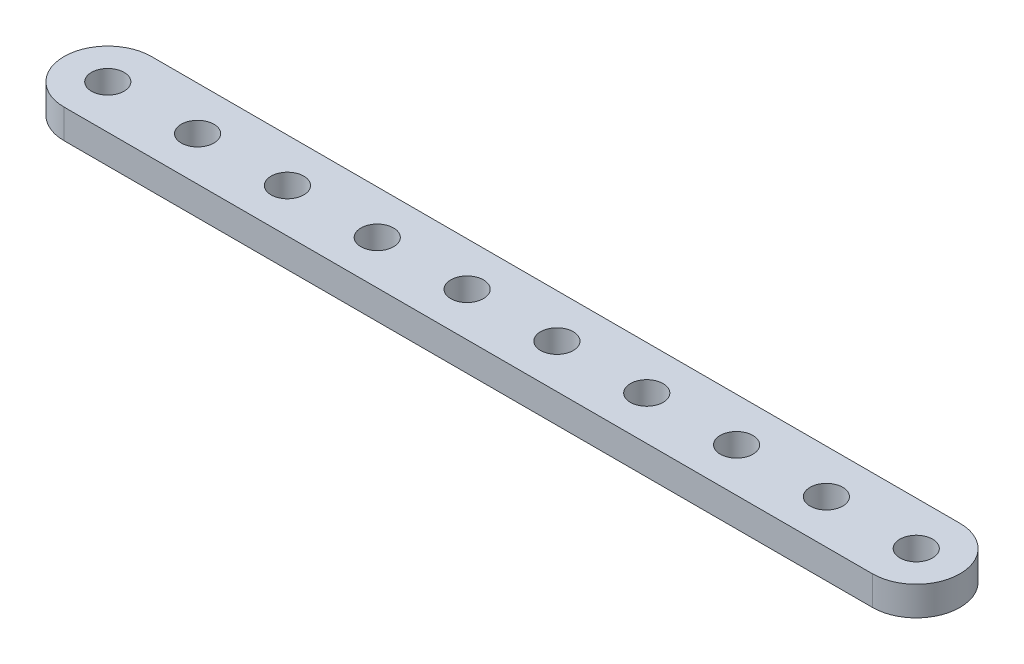
SolidWorks part; units mm, degrees
ref_plane "Front Plane" through (0, 0, 0) normal (0, 0, 1) x (1, 0, 0)
ref_plane "Top Plane" through (0, 0, 0) normal (0, 1, 0) x (1, 0, 0)
ref_plane "Right Plane" through (0, 0, 0) normal (1, 0, 0) x (0, 0, -1)
ref_plane "Plane1" through (0, 0, 0) normal (0, -1, 0) x (1, 0, 0)
sketch "Sketch1" plane through (0, 0, 0) normal (0, -1, 0) x (1, 0, 0)
  line L0 (-48.895, -4.7625) -> (48.895, -4.7625)
  line L1 (48.895, 4.7625) -> (-48.895, 4.7625)
  arc A0 (48.895, -4.7625) -> (48.895, 4.7625) centre (48.895, 0) ccw
  arc A1 (-48.895, 4.7625) -> (-48.895, -4.7625) centre (-48.895, 0) ccw
  circle A2 centre (48.895, 0) radius 1.778
  circle A3 centre (39.116, 0) radius 1.778
  circle A4 centre (29.337, 0) radius 1.778
  circle A5 centre (19.558, 0) radius 1.778
  circle A6 centre (9.779, 0) radius 1.778
  circle A7 centre (0, 0) radius 1.778
  circle A8 centre (-9.779, 0) radius 1.778
  circle A9 centre (-19.558, 0) radius 1.778
  circle A10 centre (-29.337, 0) radius 1.778
  circle A11 centre (-39.116, 0) radius 1.778
  circle A12 centre (-48.895, 0) radius 1.778
extrude "Boss-Extrude1" add sketch "Sketch1" against normal blind 6.35
sketch "Sketch2" plane through (0, 6.35, 0) normal (0, 1, 0) x (1, 0, 0)
  line L0 (48.895, -4.7625) -> (-48.895, -4.7625) construction
  line L1 (-48.895, 4.7625) -> (48.895, 4.7625) construction
  line L2 (-39.116, -4.7625) -> (-55.6151, -6.9414)
  line L3 (-55.6151, -6.9414) -> (-55.6151, 8.9982)
  line L4 (-55.6151, 8.9982) -> (-39.116, 4.7625)
  arc A0 (-39.116, -4.7625) -> (-39.116, 4.7625) centre (-39.116, 0) cw
  circle A1 centre (-39.116, 0) radius 1.778 construction
  dimension "D1" = 4.7625
  dimension "D2" = 0
extrude "Cut-Extrude1" cut sketch "Sketch2" against normal through all
sketch "Sketch3" plane through (0, 6.35, 0) normal (0, 1, 0) x (1, 0, 0)
  line L1 (-60.4598, -33.9547) -> (63.5017, -33.9547)
  line L2 (-60.4598, -33.9547) -> (-60.4598, 23.1754)
  line L3 (-60.4598, 23.1754) -> (63.5017, 23.1754)
  line L4 (63.5017, -33.9547) -> (63.5017, 23.1754)
extrude "Cut-Extrude2" cut sketch "Sketch3" against normal blind 3.175
